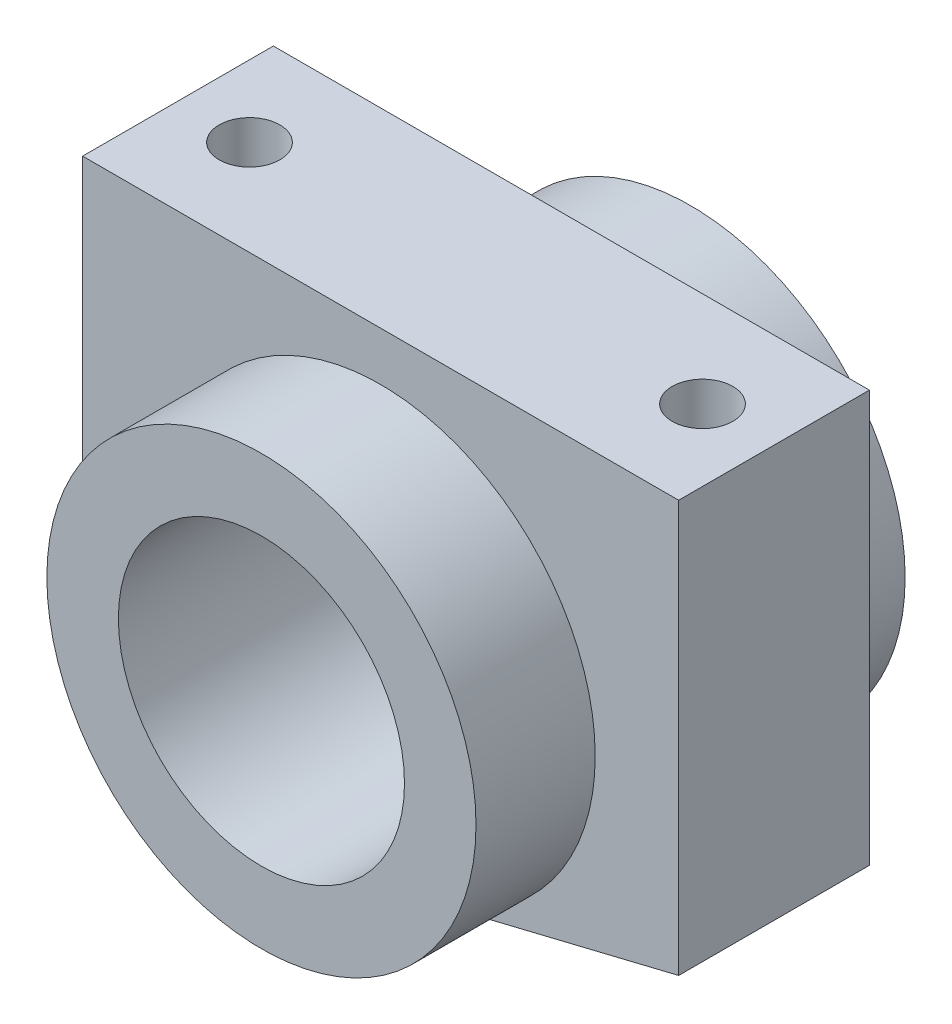
SolidWorks part; units mm, degrees
ref_plane "Front Plane" through (0, 0, 0) normal (0, 0, 1) x (1, 0, 0)
ref_plane "Top Plane" through (0, 0, 0) normal (0, 1, 0) x (1, 0, 0)
ref_plane "Right Plane" through (0, 0, 0) normal (1, 0, 0) x (0, 0, -1)
sketch "Sketch1" plane through (0, 0, 0) normal (0, 0, 1) x (1, 0, 0)
  line L0 (19.8438, 0) -> (-19.8438, 0)
  line L1 (-19.8438, 0) -> (-19.8437, -17.4625)
  line L2 (-19.8437, -17.4625) -> (-19.8437, -27.4061)
  line L3 (0, 11.7335) -> (0, -27.0585) construction
  line L4 (-19.8437, -27.4061) -> (0, -32.2386)
  line L5 (19.8438, 0) -> (19.8437, -17.4625)
  line L6 (19.8437, -27.4061) -> (0, -32.2386)
  line L7 (19.8437, -17.4625) -> (19.8437, -27.4061)
  circle A0 centre (0, -17.5335) radius 9.525
  point P12 (0, 0)
  dimension "D1" = 39.6875
  dimension "D2" = 17.4625
extrude "Boss-Extrude2" add sketch "Sketch1" along normal mid plane 12.7
sketch "Sketch2" plane through (0, 0, 0) normal (0, 0, 1) x (1, 0, 0)
  circle A0 centre (0, -17.5335) radius 14.2875
  circle A1 centre (0, -17.5335) radius 9.525 construction
  circle A2 centre (0, -17.5335) radius 9.525
extrude "Boss-Extrude3" add sketch "Sketch2" along normal mid plane 28.575
sketch "Sketch6" plane through (0, 0, 0) normal (0, 1, 0) x (1, 0, 0)
  line L0 (0, -15.7163) -> (0, 15.7163) construction
  circle A0 centre (-15.0812, 0) radius 2.0193
  circle A1 centre (15.0812, 0) radius 2.0193
  dimension "D1" = 15.0812
extrude "Cut-Extrude1" cut sketch "Sketch6" against normal blind 17.4625
ref_plane "Plane1" through (0, -17.4625, 0) normal (0, 1, 0) x (1, 0, 0)
ref_plane "Plane2" through (0, -31.75, 0) normal (0, 1, 0) x (1, 0, 0)
sketch "Sketch9" plane through (0, -17.4625, 0) normal (0, 1, 0) x (1, 0, 0)
  line L0 (0, -15.7163) -> (0, 15.7163) construction
  circle A0 centre (-15.0812, 0) radius 2.0193
  circle A1 centre (15.0812, 0) radius 2.0193
extrude "Cut-Extrude2" cut sketch "Sketch9" against normal through all both and the other way through all
